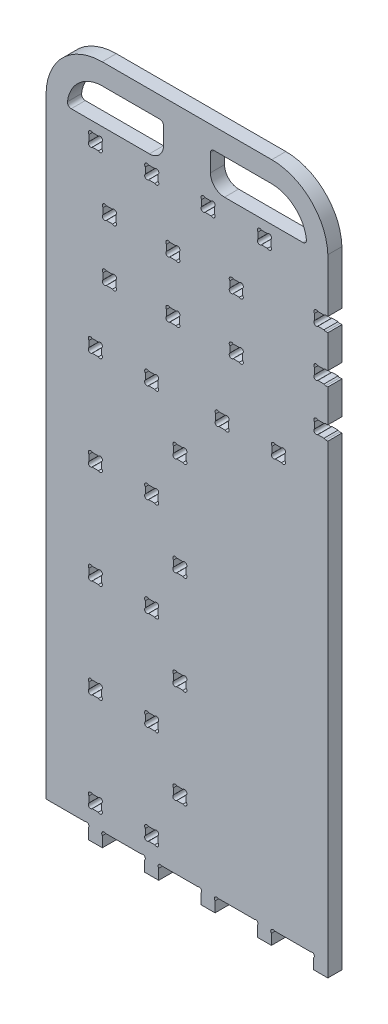
SolidWorks part; units mm, degrees
ref_plane "Front Plane" through (0, 0, 0) normal (0, 0, 1) x (1, 0, 0)
ref_plane "Top Plane" through (0, 0, 0) normal (0, 1, 0) x (1, 0, 0)
ref_plane "Right Plane" through (0, 0, 0) normal (1, 0, 0) x (0, 0, -1)
sketch "Sketch1" plane through (0, 0, 0) normal (0, 0, 1) x (1, 0, 0)
  line L0 (75.8659, 869.6639) -> (305.1742, 869.6639)
  line L1 (381, 796.264) -> (381, 723.9341)
  line L11 (381, -50.8) -> (361.8551, -50.8)
  line L12 (361.8551, -50.8) -> (361.8551, -36.587)
  line L13 (308.7839, -31.75) -> (357.7764, -31.75)
  line L14 (304.7051, -50.8) -> (304.7051, -36.587)
  line L15 (285.6551, -50.8) -> (285.6551, -36.587)
  line L16 (232.5839, -31.75) -> (281.5764, -31.75)
  line L17 (228.5051, -50.8) -> (228.5051, -36.587)
  line L18 (209.4551, -50.8) -> (209.4551, -36.587)
  line L19 (156.3839, -31.75) -> (205.3764, -31.75)
  line L20 (152.3051, -50.8) -> (152.3051, -36.587)
  line L22 (80.1839, -31.75) -> (129.1764, -31.75)
  line L23 (76.1051, -50.8) -> (76.1051, -36.587)
  line L24 (57.0551, -50.8) -> (57.0551, -36.587)
  line L25 (381, -50.8) -> (381, 577.8841)
  line L26 (52.9764, -31.75) -> (0, -31.75)
  line L27 (381, 704.8841) -> (381, 660.4341)
  line L28 (0, -31.75) -> (0, 793.75)
  line L29 (158.75, 812.8) -> (158.75, 836.295)
  line L30 (153.67, 841.375) -> (76.2, 841.375)
  line L31 (33.9594, 793.75) -> (139.7, 793.75)
  line L32 (227.33, 841.375) -> (304.8, 841.375)
  line L33 (347.0406, 793.75) -> (241.3, 793.75)
  line L34 (222.25, 812.8) -> (222.25, 836.295)
  line L35 (133.2551, -50.8) -> (133.2551, -36.587)
  line L147 (285.6551, -50.8) -> (304.7051, -50.8)
  line L148 (209.4551, -50.8) -> (228.5051, -50.8)
  line L149 (133.2551, -50.8) -> (152.3051, -50.8)
  line L150 (57.0551, -50.8) -> (76.1051, -50.8)
  line L152 (381, 641.3841) -> (381, 596.9341)
  line L154 (-0.0949, -50.8) -> (-0.0949, -36.587) [skipped]
  line L155 (3.9839, -31.75) -> (52.9764, -31.75) [skipped]
  line L179 (133.2551, -50.8) -> (133.2551, -36.587) [skipped]
  line L261 (57.0551, 139.7) -> (76.1051, 120.65) construction
  line L262 (57.9441, 121.539) -> (75.2161, 121.539)
  line L263 (57.9441, 121.539) -> (57.9441, 138.811)
  line L264 (57.9441, 138.811) -> (75.2161, 138.811)
  line L265 (75.2161, 121.539) -> (75.2161, 138.811)
  line L266 (57.9441, 126.0291) -> (62.4343, 121.539) construction
  line L267 (171.3551, 73.025) -> (190.4051, 53.975) construction
  line L268 (172.2441, 54.864) -> (189.5161, 54.864)
  line L269 (172.2441, 54.864) -> (172.2441, 72.136)
  line L270 (172.2441, 72.136) -> (189.5161, 72.136)
  line L271 (57.9441, 254.889) -> (75.2161, 254.889)
  line L272 (57.9441, 254.889) -> (57.9441, 272.161)
  line L273 (57.9441, 272.161) -> (75.2161, 272.161)
  line L274 (75.2161, 254.889) -> (75.2161, 272.161)
  line L275 (57.0551, 273.05) -> (76.1051, 254) construction
  line L276 (57.9441, 259.3791) -> (62.4343, 254.889) construction
  line L277 (57.9441, 388.239) -> (75.2161, 388.239)
  line L278 (57.9441, 388.239) -> (57.9441, 405.511)
  line L279 (57.9441, 405.511) -> (75.2161, 405.511)
  line L280 (75.2161, 388.239) -> (75.2161, 405.511)
  line L281 (57.0551, 406.4) -> (76.1051, 387.35) construction
  line L282 (57.9441, 392.7291) -> (62.4343, 388.239) construction
  line L283 (57.9441, 521.589) -> (75.2161, 521.589)
  line L284 (57.9441, 521.589) -> (57.9441, 538.861)
  line L285 (57.9441, 538.861) -> (75.2161, 538.861)
  line L286 (75.2161, 521.589) -> (75.2161, 538.861)
  line L287 (57.0551, 539.75) -> (76.1051, 520.7) construction
  line L288 (57.9441, 526.0791) -> (62.4343, 521.589) construction
  line L289 (189.5161, 54.864) -> (189.5161, 72.136)
  line L290 (171.3551, 73.025) -> (190.4051, 53.975) construction
  line L291 (172.2441, 59.3541) -> (176.7343, 54.864) construction
  line L292 (172.2441, 188.214) -> (189.5161, 188.214)
  line L293 (172.2441, 188.214) -> (172.2441, 205.486)
  line L294 (172.2441, 205.486) -> (189.5161, 205.486)
  line L295 (189.5161, 188.214) -> (189.5161, 205.486)
  line L296 (171.3551, 206.375) -> (190.4051, 187.325) construction
  line L297 (171.3551, 206.375) -> (190.4051, 187.325) construction
  line L298 (172.2441, 192.7041) -> (176.7343, 188.214) construction
  line L299 (172.2441, 321.564) -> (189.5161, 321.564)
  line L300 (172.2441, 321.564) -> (172.2441, 338.836)
  line L301 (57.9441, -11.811) -> (75.2161, -11.811)
  line L302 (57.9441, -11.811) -> (57.9441, 5.461)
  line L303 (57.9441, 5.461) -> (75.2161, 5.461)
  line L304 (75.2161, -11.811) -> (75.2161, 5.461)
  line L305 (57.0551, 6.35) -> (76.1051, -12.7) construction
  line L306 (57.9441, -7.3209) -> (62.4343, -11.811) construction
  line L307 (172.2441, 338.836) -> (189.5161, 338.836)
  line L308 (189.5161, 321.564) -> (189.5161, 338.836)
  line L309 (171.3551, 339.725) -> (190.4051, 320.675) construction
  line L310 (171.3551, 339.725) -> (190.4051, 320.675) construction
  line L311 (172.2441, 326.0541) -> (176.7343, 321.564) construction
  line L312 (172.2441, 454.914) -> (189.5161, 454.914)
  line L313 (172.2441, 454.914) -> (172.2441, 472.186)
  line L314 (172.2441, 472.186) -> (189.5161, 472.186)
  line L315 (189.5161, 454.914) -> (189.5161, 472.186)
  line L316 (171.3551, 473.075) -> (190.4051, 454.025) construction
  line L317 (171.3551, 473.075) -> (190.4051, 454.025) construction
  line L318 (172.2441, 459.4041) -> (176.7343, 454.914) construction
  line L319 (134.1441, 121.539) -> (151.4161, 121.539)
  line L320 (134.1441, 121.539) -> (134.1441, 138.811)
  line L321 (134.1441, 138.811) -> (151.4161, 138.811)
  line L322 (151.4161, 121.539) -> (151.4161, 138.811)
  line L323 (134.1441, 254.889) -> (151.4161, 254.889)
  line L324 (134.1441, 254.889) -> (134.1441, 272.161)
  line L325 (134.1441, 272.161) -> (151.4161, 272.161)
  line L326 (151.4161, 254.889) -> (151.4161, 272.161)
  line L327 (134.1441, 388.239) -> (151.4161, 388.239)
  line L328 (134.1441, 388.239) -> (134.1441, 405.511)
  line L329 (134.1441, 405.511) -> (151.4161, 405.511)
  line L330 (151.4161, 388.239) -> (151.4161, 405.511)
  line L331 (134.1441, 521.589) -> (151.4161, 521.589)
  line L332 (134.1441, 521.589) -> (134.1441, 538.861)
  line L333 (134.1441, 538.861) -> (151.4161, 538.861)
  line L334 (151.4161, 521.589) -> (151.4161, 538.861)
  line L335 (134.1441, -11.811) -> (151.4161, -11.811)
  line L336 (134.1441, -11.811) -> (134.1441, 5.461)
  line L337 (134.1441, 5.461) -> (151.4161, 5.461)
  line L338 (151.4161, -11.811) -> (151.4161, 5.461)
  line L339 (133.2551, 139.7) -> (152.3051, 120.65) construction
  line L340 (134.1441, 126.0291) -> (138.6343, 121.539) construction
  line L341 (133.2551, 273.05) -> (152.3051, 254) construction
  line L342 (134.1441, 259.3791) -> (138.6343, 254.889) construction
  line L343 (133.2551, 406.4) -> (152.3051, 387.35) construction
  line L344 (134.1441, 392.7291) -> (138.6343, 388.239) construction
  line L345 (133.2551, 539.75) -> (152.3051, 520.7) construction
  line L346 (134.1441, 526.0791) -> (138.6343, 521.589) construction
  line L347 (133.2551, 6.35) -> (152.3051, -12.7) construction
  line L348 (134.1441, -7.3209) -> (138.6343, -11.811) construction
  line L349 (76.2, 628.65) -> (95.25, 609.6) construction
  line L350 (77.089, 610.489) -> (94.361, 610.489)
  line L351 (77.089, 610.489) -> (77.089, 627.761)
  line L352 (77.089, 627.761) -> (94.361, 627.761)
  line L353 (94.361, 610.489) -> (94.361, 627.761)
  line L354 (76.2, 628.65) -> (95.25, 609.6) construction
  line L355 (77.089, 614.9791) -> (81.5791, 610.489) construction
  line L356 (285.75, 781.05) -> (304.8, 762) construction
  line L357 (286.639, 762.889) -> (303.911, 762.889)
  line L358 (286.639, 762.889) -> (286.639, 780.161)
  line L359 (286.639, 780.161) -> (303.911, 780.161)
  line L360 (162.814, 610.489) -> (180.086, 610.489)
  line L361 (162.814, 610.489) -> (162.814, 627.761)
  line L362 (162.814, 627.761) -> (180.086, 627.761)
  line L363 (180.086, 610.489) -> (180.086, 627.761)
  line L364 (161.925, 628.65) -> (180.975, 609.6) construction
  line L365 (161.925, 628.65) -> (180.975, 609.6) construction
  line L366 (162.814, 614.9791) -> (167.3041, 610.489) construction
  line L367 (248.539, 610.489) -> (265.811, 610.489)
  line L368 (248.539, 610.489) -> (248.539, 627.761)
  line L369 (248.539, 627.761) -> (265.811, 627.761)
  line L370 (265.811, 610.489) -> (265.811, 627.761)
  line L371 (247.65, 628.65) -> (266.7, 609.6) construction
  line L372 (247.65, 628.65) -> (266.7, 609.6) construction
  line L373 (248.539, 614.9791) -> (253.0291, 610.489) construction
  line L374 (162.814, 686.689) -> (180.086, 686.689)
  line L375 (162.814, 686.689) -> (162.814, 703.961)
  line L376 (162.814, 703.961) -> (180.086, 703.961)
  line L377 (180.086, 686.689) -> (180.086, 703.961)
  line L378 (161.925, 704.85) -> (180.975, 685.8) construction
  line L379 (161.925, 704.85) -> (180.975, 685.8) construction
  line L380 (162.814, 691.1791) -> (167.3041, 686.689) construction
  line L381 (248.539, 686.689) -> (265.811, 686.689)
  line L382 (248.539, 686.689) -> (248.539, 703.961)
  line L383 (248.539, 703.961) -> (265.811, 703.961)
  line L384 (265.811, 686.689) -> (265.811, 703.961)
  line L385 (247.65, 704.85) -> (266.7, 685.8) construction
  line L386 (247.65, 704.85) -> (266.7, 685.8) construction
  line L387 (248.539, 691.1791) -> (253.0291, 686.689) construction
  line L388 (77.089, 686.689) -> (94.361, 686.689)
  line L389 (77.089, 686.689) -> (77.089, 703.961)
  line L390 (77.089, 703.961) -> (94.361, 703.961)
  line L391 (94.361, 686.689) -> (94.361, 703.961)
  line L392 (76.2, 704.85) -> (95.25, 685.8) construction
  line L393 (76.2, 704.85) -> (95.25, 685.8) construction
  line L394 (77.089, 691.1791) -> (81.5791, 686.689) construction
  line L395 (303.911, 762.889) -> (303.911, 780.161)
  line L396 (285.75, 781.05) -> (304.8, 762) construction
  line L397 (286.639, 767.3791) -> (291.1291, 762.889) construction
  line L398 (210.439, 762.889) -> (227.711, 762.889)
  line L399 (210.439, 762.889) -> (210.439, 780.161)
  line L400 (210.439, 780.161) -> (227.711, 780.161)
  line L401 (227.711, 762.889) -> (227.711, 780.161)
  line L402 (209.55, 781.05) -> (228.6, 762) construction
  line L403 (209.55, 781.05) -> (228.6, 762) construction
  line L404 (210.439, 767.3791) -> (214.9291, 762.889) construction
  line L405 (134.239, 762.889) -> (151.511, 762.889)
  line L406 (134.239, 762.889) -> (134.239, 780.161)
  line L407 (134.239, 780.161) -> (151.511, 780.161)
  line L408 (151.511, 762.889) -> (151.511, 780.161)
  line L409 (133.35, 781.05) -> (152.4, 762) construction
  line L410 (133.35, 781.05) -> (152.4, 762) construction
  line L411 (134.239, 767.3791) -> (138.7291, 762.889) construction
  line L412 (58.039, 762.889) -> (75.311, 762.889)
  line L413 (58.039, 762.889) -> (58.039, 780.161)
  line L414 (58.039, 780.161) -> (75.311, 780.161)
  line L415 (75.311, 762.889) -> (75.311, 780.161)
  line L416 (57.15, 781.05) -> (76.2, 762) construction
  line L417 (57.15, 781.05) -> (76.2, 762) construction
  line L418 (58.039, 767.3791) -> (62.5291, 762.889) construction
  line L419 (366.4401, 641.3841) -> (376.884, 660.4341) construction
  line L420 (75.8659, 869.6639) -> (354.8946, 869.6639)
  line L421 (363.0261, 642.2731) -> (380.2981, 642.2731)
  line L422 (363.0261, 642.2731) -> (363.0261, 659.5451)
  line L423 (363.0261, 659.5451) -> (380.2981, 659.5451)
  line L424 (380.2981, 642.2731) -> (380.2981, 659.5451)
  line L425 (363.0261, 646.7632) -> (367.5162, 642.2731) construction
  line L426 (247.5551, 520.5623) -> (228.5051, 539.6123) construction
  line L427 (229.3941, 521.4513) -> (246.6661, 521.4513)
  line L428 (378.053, 660.475) -> (381, 660.4341)
  line L429 (381, 641.3841) -> (378.053, 641.3432)
  line L430 (366.4401, 577.8841) -> (376.884, 596.9341) construction
  line L431 (366.4401, 704.8841) -> (376.884, 723.9341) construction
  line L432 (363.0261, 705.7731) -> (380.2981, 705.7731)
  line L433 (363.0261, 705.7731) -> (363.0261, 723.0451)
  line L434 (363.0261, 723.0451) -> (380.2981, 723.0451)
  line L435 (380.2981, 705.7731) -> (380.2981, 723.0451)
  line L436 (363.0261, 710.2632) -> (367.5162, 705.7731) construction
  line L437 (378.053, 723.975) -> (381, 723.9341)
  line L438 (381, 704.8841) -> (378.053, 704.8432)
  line L439 (363.0261, 578.7731) -> (380.2981, 578.7731)
  line L440 (363.0261, 578.7731) -> (363.0261, 596.0451)
  line L441 (363.0261, 596.0451) -> (380.2981, 596.0451)
  line L442 (380.2981, 578.7731) -> (380.2981, 596.0451)
  line L443 (363.0261, 583.2632) -> (367.5162, 578.7731) construction
  line L444 (378.053, 596.975) -> (381, 596.9341)
  line L445 (381, 577.8841) -> (378.053, 577.8432)
  line L446 (229.3941, 521.4513) -> (229.3941, 538.7233)
  line L447 (229.3941, 538.7233) -> (246.6661, 538.7233)
  line L448 (246.6661, 521.4513) -> (246.6661, 538.7233)
  line L449 (229.3941, 525.9414) -> (233.8843, 521.4513) construction
  line L450 (304.7051, 520.5623) -> (323.7551, 539.6123) construction
  line L451 (305.5941, 521.4513) -> (322.8661, 521.4513)
  line L452 (305.5941, 521.4513) -> (305.5941, 538.7233)
  line L453 (305.5941, 538.7233) -> (322.8661, 538.7233)
  line L454 (322.8661, 521.4513) -> (322.8661, 538.7233)
  line L455 (305.5941, 525.9414) -> (310.0843, 521.4513) construction
  arc A0 (0, 793.75) -> (75.8659, 869.6639) centre (75.8659, 793.798) cw
  arc A1 (305.1742, 869.6639) -> (381, 796.264) centre (305.1742, 793.798) cw
  arc A14 (361.8551, -36.587) -> (357.7764, -31.75) centre (359.6101, -34.342) ccw
  arc A15 (308.7839, -31.75) -> (304.7051, -36.587) centre (306.9502, -34.342) ccw
  arc A16 (285.6551, -36.587) -> (281.5764, -31.75) centre (283.4101, -34.342) ccw
  arc A17 (232.5839, -31.75) -> (228.5051, -36.587) centre (230.7502, -34.342) ccw
  arc A18 (209.4551, -36.587) -> (205.3764, -31.75) centre (207.2101, -34.342) ccw
  arc A19 (156.3839, -31.75) -> (152.3051, -36.587) centre (154.5502, -34.342) ccw
  arc A20 (133.2551, -36.587) -> (129.1764, -31.75) centre (131.0101, -34.342) ccw
  arc A21 (80.1839, -31.75) -> (76.1051, -36.587) centre (78.3502, -34.342) ccw
  arc A22 (57.0551, -36.587) -> (52.9764, -31.75) centre (54.8101, -34.342) ccw
  arc A23 (158.75, 836.295) -> (153.67, 841.375) centre (153.67, 836.295) ccw
  arc A25 (76.2, 841.375) -> (28.9157, 799.4366) centre (76.2, 793.75) ccw
  arc A27 (139.7, 793.75) -> (158.75, 812.8) centre (139.7, 812.8) ccw
  arc A28 (304.8, 841.375) -> (352.0843, 799.4366) centre (304.8, 793.75) cw
  arc A29 (241.3, 793.75) -> (222.25, 812.8) centre (241.3, 812.8) cw
  arc A30 (352.0843, 799.4366) -> (347.0406, 793.75) centre (347.0406, 798.83) cw
  arc A31 (222.25, 836.295) -> (227.33, 841.375) centre (227.33, 836.295) cw
  arc A32 (33.9594, 793.75) -> (28.9157, 799.4366) centre (33.9594, 798.83) cw
  arc A154 (3.9839, -31.75) -> (-0.0949, -36.587) centre (2.1502, -34.342) ccw [skipped]
  arc A305 (57.9441, 134.3209) -> (62.4343, 138.811) centre (60.1892, 136.5659) cw
  arc A306 (70.726, 138.811) -> (75.2161, 134.3209) centre (72.9711, 136.5659) cw
  arc A307 (57.9441, 126.0291) -> (62.4343, 121.539) centre (60.1892, 123.7841) ccw
  arc A308 (75.2161, 126.0291) -> (70.726, 121.539) centre (72.9711, 123.7841) cw
  arc A309 (172.2441, 67.6459) -> (176.7343, 72.136) centre (174.4892, 69.8909) cw
  arc A310 (185.026, 72.136) -> (189.5161, 67.6459) centre (187.2711, 69.8909) cw
  arc A311 (172.2441, 59.3541) -> (176.7343, 54.864) centre (174.4892, 57.1091) ccw
  arc A312 (189.5161, 59.3541) -> (185.026, 54.864) centre (187.2711, 57.1091) cw
  arc A313 (57.9441, 267.6709) -> (62.4343, 272.161) centre (60.1892, 269.9159) cw
  arc A314 (70.726, 272.161) -> (75.2161, 267.6709) centre (72.9711, 269.9159) cw
  arc A315 (57.9441, 259.3791) -> (62.4343, 254.889) centre (60.1892, 257.1341) ccw
  arc A316 (75.2161, 259.3791) -> (70.726, 254.889) centre (72.9711, 257.1341) cw
  arc A317 (57.9441, 401.0209) -> (62.4343, 405.511) centre (60.1892, 403.2659) cw
  arc A318 (70.726, 405.511) -> (75.2161, 401.0209) centre (72.9711, 403.2659) cw
  arc A319 (57.9441, 392.7291) -> (62.4343, 388.239) centre (60.1892, 390.4841) ccw
  arc A320 (75.2161, 392.7291) -> (70.726, 388.239) centre (72.9711, 390.4841) cw
  arc A321 (57.9441, 534.3709) -> (62.4343, 538.861) centre (60.1892, 536.6159) cw
  arc A322 (70.726, 538.861) -> (75.2161, 534.3709) centre (72.9711, 536.6159) cw
  arc A323 (57.9441, 526.0791) -> (62.4343, 521.589) centre (60.1892, 523.8341) ccw
  arc A324 (75.2161, 526.0791) -> (70.726, 521.589) centre (72.9711, 523.8341) cw
  arc A325 (172.2441, 200.9959) -> (176.7343, 205.486) centre (174.4892, 203.2409) cw
  arc A326 (185.026, 205.486) -> (189.5161, 200.9959) centre (187.2711, 203.2409) cw
  arc A327 (172.2441, 192.7041) -> (176.7343, 188.214) centre (174.4892, 190.4591) ccw
  arc A328 (189.5161, 192.7041) -> (185.026, 188.214) centre (187.2711, 190.4591) cw
  arc A329 (172.2441, 334.3459) -> (176.7343, 338.836) centre (174.4892, 336.5909) cw
  arc A330 (185.026, 338.836) -> (189.5161, 334.3459) centre (187.2711, 336.5909) cw
  arc A331 (172.2441, 326.0541) -> (176.7343, 321.564) centre (174.4892, 323.8091) ccw
  arc A332 (189.5161, 326.0541) -> (185.026, 321.564) centre (187.2711, 323.8091) cw
  arc A333 (172.2441, 467.6959) -> (176.7343, 472.186) centre (174.4892, 469.9409) cw
  arc A334 (185.026, 472.186) -> (189.5161, 467.6959) centre (187.2711, 469.9409) cw
  arc A335 (172.2441, 459.4041) -> (176.7343, 454.914) centre (174.4892, 457.1591) ccw
  arc A336 (189.5161, 459.4041) -> (185.026, 454.914) centre (187.2711, 457.1591) cw
  arc A337 (57.9441, 0.9709) -> (62.4343, 5.461) centre (60.1892, 3.2159) cw
  arc A338 (70.726, 5.461) -> (75.2161, 0.9709) centre (72.9711, 3.2159) cw
  arc A339 (57.9441, -7.3209) -> (62.4343, -11.811) centre (60.1892, -9.5659) ccw
  arc A340 (75.2161, -7.3209) -> (70.726, -11.811) centre (72.9711, -9.5659) cw
  arc A341 (77.089, 623.2709) -> (81.5791, 627.761) centre (79.3341, 625.5159) cw
  arc A342 (89.8709, 627.761) -> (94.361, 623.2709) centre (92.1159, 625.5159) cw
  arc A343 (77.089, 614.9791) -> (81.5791, 610.489) centre (79.3341, 612.7341) ccw
  arc A344 (94.361, 614.9791) -> (89.8709, 610.489) centre (92.1159, 612.7341) cw
  arc A345 (162.814, 623.2709) -> (167.3041, 627.761) centre (165.0591, 625.5159) cw
  arc A346 (175.5959, 627.761) -> (180.086, 623.2709) centre (177.8409, 625.5159) cw
  arc A347 (162.814, 614.9791) -> (167.3041, 610.489) centre (165.0591, 612.7341) ccw
  arc A348 (180.086, 614.9791) -> (175.5959, 610.489) centre (177.8409, 612.7341) cw
  arc A349 (248.539, 623.2709) -> (253.0291, 627.761) centre (250.7841, 625.5159) cw
  arc A350 (134.1441, 134.3209) -> (138.6343, 138.811) centre (136.3892, 136.5659) cw
  arc A351 (146.926, 138.811) -> (151.4161, 134.3209) centre (149.1711, 136.5659) cw
  arc A352 (134.1441, 126.0291) -> (138.6343, 121.539) centre (136.3892, 123.7841) ccw
  arc A353 (151.4161, 126.0291) -> (146.926, 121.539) centre (149.1711, 123.7841) cw
  arc A354 (134.1441, 267.6709) -> (138.6343, 272.161) centre (136.3892, 269.9159) cw
  arc A355 (146.926, 272.161) -> (151.4161, 267.6709) centre (149.1711, 269.9159) cw
  arc A356 (134.1441, 259.3791) -> (138.6343, 254.889) centre (136.3892, 257.1341) ccw
  arc A357 (151.4161, 259.3791) -> (146.926, 254.889) centre (149.1711, 257.1341) cw
  arc A358 (134.1441, 401.0209) -> (138.6343, 405.511) centre (136.3892, 403.2659) cw
  arc A359 (146.926, 405.511) -> (151.4161, 401.0209) centre (149.1711, 403.2659) cw
  arc A360 (134.1441, 392.7291) -> (138.6343, 388.239) centre (136.3892, 390.4841) ccw
  arc A361 (151.4161, 392.7291) -> (146.926, 388.239) centre (149.1711, 390.4841) cw
  arc A362 (134.1441, 534.3709) -> (138.6343, 538.861) centre (136.3892, 536.6159) cw
  arc A363 (146.926, 538.861) -> (151.4161, 534.3709) centre (149.1711, 536.6159) cw
  arc A364 (134.1441, 526.0791) -> (138.6343, 521.589) centre (136.3892, 523.8341) ccw
  arc A365 (151.4161, 526.0791) -> (146.926, 521.589) centre (149.1711, 523.8341) cw
  arc A366 (134.1441, 0.9709) -> (138.6343, 5.461) centre (136.3892, 3.2159) cw
  arc A367 (146.926, 5.461) -> (151.4161, 0.9709) centre (149.1711, 3.2159) cw
  arc A368 (134.1441, -7.3209) -> (138.6343, -11.811) centre (136.3892, -9.5659) ccw
  arc A369 (151.4161, -7.3209) -> (146.926, -11.811) centre (149.1711, -9.5659) cw
  arc A370 (286.639, 775.6709) -> (291.1291, 780.161) centre (288.8841, 777.9159) cw
  arc A371 (299.4209, 780.161) -> (303.911, 775.6709) centre (301.6659, 777.9159) cw
  arc A372 (286.639, 767.3791) -> (291.1291, 762.889) centre (288.8841, 765.1341) ccw
  arc A373 (303.911, 767.3791) -> (299.4209, 762.889) centre (301.6659, 765.1341) cw
  arc A374 (261.3209, 627.761) -> (265.811, 623.2709) centre (263.5659, 625.5159) cw
  arc A375 (248.539, 614.9791) -> (253.0291, 610.489) centre (250.7841, 612.7341) ccw
  arc A376 (265.811, 614.9791) -> (261.3209, 610.489) centre (263.5659, 612.7341) cw
  arc A377 (162.814, 699.4709) -> (167.3041, 703.961) centre (165.0591, 701.7159) cw
  arc A378 (175.5959, 703.961) -> (180.086, 699.4709) centre (177.8409, 701.7159) cw
  arc A379 (162.814, 691.1791) -> (167.3041, 686.689) centre (165.0591, 688.9341) ccw
  arc A380 (180.086, 691.1791) -> (175.5959, 686.689) centre (177.8409, 688.9341) cw
  arc A381 (248.539, 699.4709) -> (253.0291, 703.961) centre (250.7841, 701.7159) cw
  arc A382 (261.3209, 703.961) -> (265.811, 699.4709) centre (263.5659, 701.7159) cw
  arc A383 (248.539, 691.1791) -> (253.0291, 686.689) centre (250.7841, 688.9341) ccw
  arc A384 (265.811, 691.1791) -> (261.3209, 686.689) centre (263.5659, 688.9341) cw
  arc A385 (77.089, 699.4709) -> (81.5791, 703.961) centre (79.3341, 701.7159) cw
  arc A386 (89.8709, 703.961) -> (94.361, 699.4709) centre (92.1159, 701.7159) cw
  arc A387 (77.089, 691.1791) -> (81.5791, 686.689) centre (79.3341, 688.9341) ccw
  arc A388 (94.361, 691.1791) -> (89.8709, 686.689) centre (92.1159, 688.9341) cw
  arc A389 (210.439, 775.6709) -> (214.9291, 780.161) centre (212.6841, 777.9159) cw
  arc A390 (223.2209, 780.161) -> (227.711, 775.6709) centre (225.4659, 777.9159) cw
  arc A391 (210.439, 767.3791) -> (214.9291, 762.889) centre (212.6841, 765.1341) ccw
  arc A392 (227.711, 767.3791) -> (223.2209, 762.889) centre (225.4659, 765.1341) cw
  arc A393 (134.239, 775.6709) -> (138.7291, 780.161) centre (136.4841, 777.9159) cw
  arc A394 (147.0209, 780.161) -> (151.511, 775.6709) centre (149.2659, 777.9159) cw
  arc A395 (134.239, 767.3791) -> (138.7291, 762.889) centre (136.4841, 765.1341) ccw
  arc A396 (151.511, 767.3791) -> (147.0209, 762.889) centre (149.2659, 765.1341) cw
  arc A397 (58.039, 775.6709) -> (62.5291, 780.161) centre (60.2841, 777.9159) cw
  arc A398 (70.8209, 780.161) -> (75.311, 775.6709) centre (73.0659, 777.9159) cw
  arc A399 (58.039, 767.3791) -> (62.5291, 762.889) centre (60.2841, 765.1341) ccw
  arc A400 (75.311, 767.3791) -> (70.8209, 762.889) centre (73.0659, 765.1341) cw
  arc A401 (363.0261, 655.055) -> (367.5162, 659.5451) centre (365.2712, 657.3) cw
  arc A402 (375.808, 659.5451) -> (380.2981, 655.055) centre (378.053, 657.3) cw
  arc A403 (363.0261, 646.7632) -> (367.5162, 642.2731) centre (365.2712, 644.5182) ccw
  arc A404 (380.2981, 646.7632) -> (375.808, 642.2731) centre (378.053, 644.5182) cw
  arc A405 (229.3941, 534.2332) -> (233.8843, 538.7233) centre (231.6392, 536.4782) cw
  arc A406 (242.176, 538.7233) -> (246.6661, 534.2332) centre (244.4211, 536.4782) cw
  arc A407 (229.3941, 525.9414) -> (233.8843, 521.4513) centre (231.6392, 523.6964) ccw
  arc A408 (246.6661, 525.9414) -> (242.176, 521.4513) centre (244.4211, 523.6964) cw
  arc A409 (363.0261, 718.555) -> (367.5162, 723.0451) centre (365.2712, 720.8) cw
  arc A410 (375.808, 723.0451) -> (380.2981, 718.555) centre (378.053, 720.8) cw
  arc A411 (363.0261, 710.2632) -> (367.5162, 705.7731) centre (365.2712, 708.0182) ccw
  arc A412 (380.2981, 710.2632) -> (375.808, 705.7731) centre (378.053, 708.0182) cw
  arc A413 (363.0261, 591.555) -> (367.5162, 596.0451) centre (365.2712, 593.8) cw
  arc A414 (375.808, 596.0451) -> (380.2981, 591.555) centre (378.053, 593.8) cw
  arc A415 (363.0261, 583.2632) -> (367.5162, 578.7731) centre (365.2712, 581.0182) ccw
  arc A416 (380.2981, 583.2632) -> (375.808, 578.7731) centre (378.053, 581.0182) cw
  arc A417 (305.5941, 534.2332) -> (310.0843, 538.7233) centre (307.8392, 536.4782) cw
  arc A418 (318.376, 538.7233) -> (322.8661, 534.2332) centre (320.6211, 536.4782) cw
  arc A419 (305.5941, 525.9414) -> (310.0843, 521.4513) centre (307.8392, 523.6964) ccw
  arc A420 (322.8661, 525.9414) -> (318.376, 521.4513) centre (320.6211, 523.6964) cw
  point P15 (142.7801, 263.525)
  point P16 (371.6621, 587.4091)
  point P35 (371.6621, 714.4091)
  point P43 (0, 0)
  point P47 (314.2301, 530.0873)
  point P48 (238.0301, 530.0873)
  point P58 (0, 0)
  point P70 (142.7801, -3.175)
  point P109 (142.7801, 130.175)
  point P125 (66.5801, 263.525)
  point P156 (66.5801, -3.175)
  point P163 (66.5801, 130.175)
  point P199 (142.7801, 396.875)
  point P213 (180.8801, 196.85)
  point P225 (142.7801, 530.225)
  point P247 (180.8801, 330.2)
  point P312 (75.2161, 130.175)
  point P313 (66.5801, 138.811)
  point P326 (66.5801, 396.875)
  point P345 (66.5801, 530.225)
  point P370 (180.8801, 63.5)
  point P383 (295.275, 771.525)
  point P398 (180.8801, 463.55)
  point P420 (219.075, 771.525)
  point P443 (142.875, 771.525)
  point P450 (171.45, 619.125)
  point P465 (85.725, 619.125)
  point P486 (257.175, 619.125)
  point P507 (171.45, 695.325)
  point P530 (257.175, 695.325)
  point P584 (85.725, 695.325)
  point P603 (66.675, 771.525)
  point P623 (371.6621, 650.9091)
  point P641 (380.2981, 650.9091)
  point P642 (371.6621, 659.5451)
  point P645 (246.6661, 530.0873)
  point P646 (238.0301, 538.7233)
  point P669 (380.2981, 714.4091)
  point P670 (371.6621, 723.0451)
  point P682 (380.2981, 587.4091)
  point P683 (371.6621, 596.0451)
  point P688 (322.8661, 530.0873)
  point P689 (314.2301, 538.7233)
  dimension "D6" = 2
  dimension "D9" = 17.272
  dimension "D18" = 3.175
  dimension "D7" = 4
  dimension "D25" = 3.175
  dimension "D32" = 3.175
  dimension "D10" = 3.175
  dimension "D14" = 6.35
  dimension "D15" = 6.35
  dimension "D21" = 6.35
  dimension "D27" = 75.8659
  dimension "D43" = 3.175
  dimension "D50" = 3.175
  dimension "D12" = 3.175
  dimension "D8" = 2
  dimension "D16" = 825.5
  dimension "D17" = 6.35
  dimension "D19" = 6.35
  dimension "D5" = 19.05
  dimension "D20" = 6.35
  dimension "D22" = 45
  dimension "D23" = 17.272
  dimension "D24" = 6.35
  dimension "D11" = 17.272
  dimension "D26" = 6.35
  dimension "D28" = 107.3245
  dimension "D29" = 279.0287
  dimension "D30" = 381
  dimension "D31" = 17.272
  dimension "D33" = 6.35
  dimension "D34" = 6.35
  dimension "D35" = 6.35
  dimension "D36" = 6.35
  dimension "D37" = 45
  dimension "D38" = 17.272
  dimension "D39" = 6.35
  dimension "D40" = 45
  dimension "D13" = 44.45
  dimension "D44" = 6.35
  dimension "D45" = 6.35
  dimension "D46" = 6.35
  dimension "D47" = 6.35
  dimension "D48" = 45
  dimension "D49" = 17.272
  dimension "D51" = 6.35
  dimension "D52" = 6.35
  dimension "D53" = 6.35
  dimension "D54" = 6.35
  dimension "D55" = 45
  dimension "D56" = 6.35
  dimension "D57" = 6.35
  dimension "D58" = 6.35
  dimension "D59" = 45
  dimension "D2" = 5
  dimension "D41" = 4
  dimension "D42" = 2
extrude "Boss-Extrude1" add sketch "Sketch1" along normal blind 19.05
